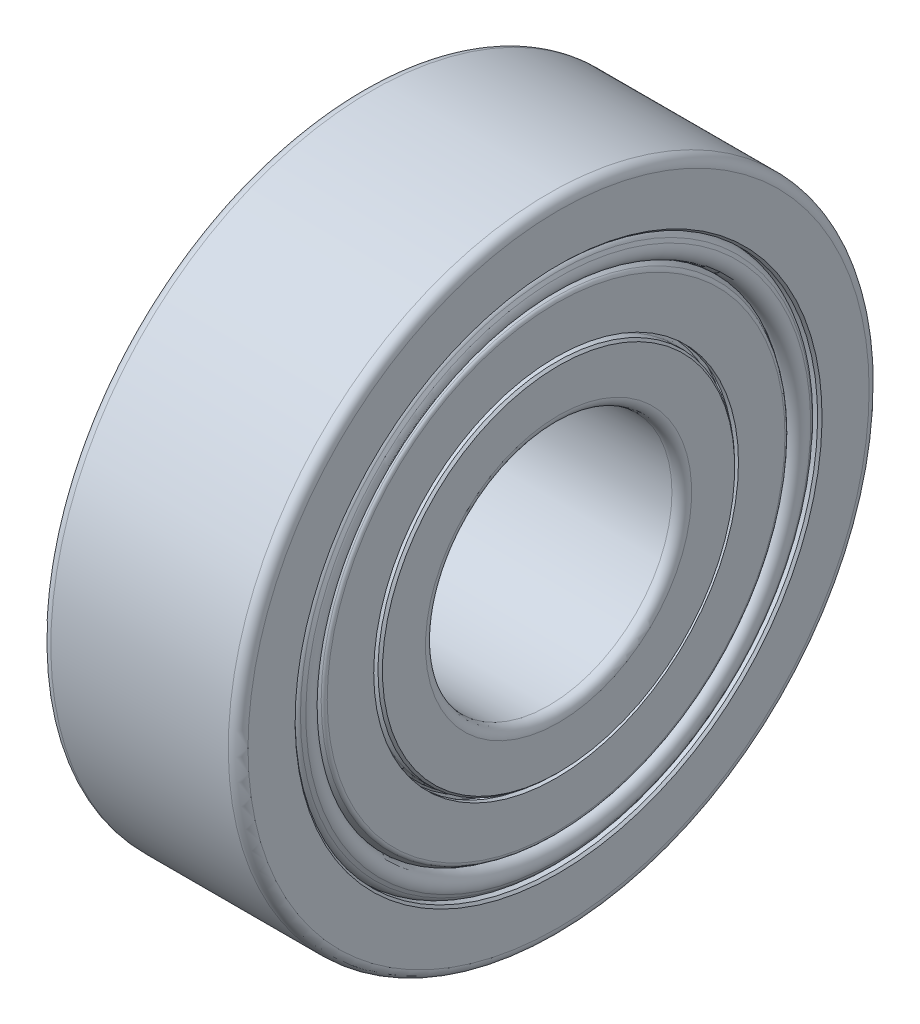
SolidWorks part; units mm, degrees
ref_plane "Front Plane" through (0, 0, 0) normal (0, 0, 1) x (1, 0, 0)
ref_plane "Top Plane" through (0, 0, 0) normal (0, 1, 0) x (1, 0, 0)
ref_plane "Right Plane" through (0, 0, 0) normal (1, 0, 0) x (0, 0, -1)
sketch "Sketch1" plane through (0, 0, 0) normal (1, 0, 0) x (0, 0, -1)
  line L0 (0, 6.5) -> (0, 6.3) construction
  line L1 (0, 2.5) -> (0, 2.7) construction
  circle A0 centre (0, 0) radius 6.5
  circle A1 centre (0, 0) radius 2.5
  circle A2 centre (0, 0) radius 5.3 construction
  circle A3 centre (0, 0) radius 3.7 construction
  dimension "OD" = 13
  dimension "ID" = 5
  dimension "Outer Ring ID" = 10.6
  dimension "Inner Ring OD" = 7.4
  dimension "Radius" = 0.2
sketch "Sketch2" plane through (0, 0, 0) normal (0, 0, 1) x (1, 0, 0)
  line L0 (-2, 6.5) -> (2, 6.5) construction
  point P3 (0, 6.5)
  dimension "Width" = 4
sketch "Sketch3" plane through (0, 0, 0) normal (0, 0, 1) x (1, 0, 0)
  line L0 (-1.8, 6.5) -> (1.8, 6.5)
  line L1 (-2, 6.3) -> (-2, 5.345)
  line L2 (2, 6.3) -> (2, 5.345)
  line L3 (-1.955, 5.3) -> (-1.7, 5.3)
  line L4 (-1.955, 3.6184) -> (-2, 3.5734)
  line L5 (-1.7891, 3.6184) -> (-1.955, 3.6184)
  line L6 (2, 5.345) -> (1.955, 5.3)
  line L7 (0, 6.5) -> (0, 5.3) construction
  line L8 (-2, 5.345) -> (-1.955, 5.3)
  line L9 (1.955, 3.6184) -> (1.955, 3.7) construction
  line L10 (-1.6625, 3.7) -> (-1.6625, 3.772)
  line L11 (-1.8, 2.5) -> (1.8, 2.5)
  line L12 (-2, 2.7) -> (-2, 3.5734)
  line L13 (2, 2.7) -> (2, 3.5734)
  line L14 (-1.6625, 3.7) -> (1.6625, 3.7) construction
  line L15 (1.6625, 3.7) -> (1.6625, 3.3667) construction
  line L16 (1.6625, 3.3667) -> (1.6625, 3.0333) construction
  line L17 (1.6625, 3.7) -> (1.6625, 3.6184) construction
  line L18 (1.6625, 3.6184) -> (1.955, 3.6184) construction
  line L19 (1.955, 3.6184) -> (2, 3.5734)
  line L20 (1.7891, 3.6184) -> (1.955, 3.6184)
  line L21 (1.6625, 3.0333) -> (1.6625, 2.7) construction
  line L22 (-1.8, 0) -> (1.8, 0) construction
  line L23 (1.7, 5.3) -> (1.7, 5.372)
  line L24 (1.7, 5.372) -> (-1.7, 5.372)
  line L25 (-1.7, 5.3) -> (-1.7, 5.372)
  line L26 (1.7, 5.3) -> (1.955, 5.3)
  line L27 (-1.6625, 3.772) -> (1.6625, 3.772)
  line L28 (1.6625, 3.772) -> (1.6625, 3.7)
  arc A0 (-2, 6.3) -> (-1.8, 6.5) centre (-1.8, 6.3) cw
  arc A1 (1.8, 6.5) -> (2, 6.3) centre (1.8, 6.3) cw
  arc A2 (-2, 2.7) -> (-1.8, 2.5) centre (-1.8, 2.7) ccw
  arc A3 (1.8, 2.5) -> (2, 2.7) centre (1.8, 2.7) ccw
  arc A4 (1.6625, 3.7) -> (1.7891, 3.6184) centre (1.7891, 3.7574) ccw
  arc A5 (-1.6625, 3.7) -> (-1.7891, 3.6184) centre (-1.7891, 3.7574) cw
  point P7 (-2, 6.5)
  point P15 (2, 6.5)
  point P30 (0, 3.7)
  point P48 (0, 5.372)
  dimension "D1" = 0.2
  dimension "D4" = 0.2
  dimension "D2" = 135
  dimension "D3" = 0.045
  dimension "D5" = 135
  dimension "D7" = 0.3375
  dimension "D9" = 0.072
  dimension "D10" = 0.3
  dimension "D8" = 0.1266
  dimension "D6" = 0.1266
revolve "Revolve1" add sketch "Sketch3" angle 360 about L22
sketch "Sketch4" plane through (0, 0, 0) normal (0, 0, 1) x (1, 0, 0)
  line L6 (1.7433, 4.9068) -> (1.6933, 4.9357) construction
  line L7 (1.6433, 5.08) -> (1.6433, 4.8837)
  line L8 (1.6533, 4.8664) -> (1.905, 4.7211)
  line L9 (1.95, 4.6431) -> (1.95, 3.7)
  line L10 (2, -6.3) -> (2, 6.3) construction
  line L11 (1.95, 3.7) -> (1.87, 3.7) construction
  line L12 (1.9233, 5.0107) -> (1.95, 5.0107) construction
  line L15 (1.6933, 4.9357) -> (1.6533, 4.8664) construction
  line L18 (1.8673, 5.14) -> (1.9073, 5.0707)
  line L20 (1.7, 5.3) -> (1.955, 5.3) construction
  arc A0 (1.6433, 5.08) -> (1.8673, 5.14) centre (1.7633, 5.08) cw
  arc A1 (1.9073, 5.0707) -> (1.7433, 4.9068) centre (1.8033, 5.0107) cw construction
  arc A2 (1.905, 4.7211) -> (1.95, 4.6431) centre (1.86, 4.6431) cw
  arc A3 (1.6433, 4.8837) -> (1.6533, 4.8664) centre (1.6633, 4.8837) ccw
  arc A4 (1.9073, 5.0707) -> (1.8033, 4.8907) centre (1.8033, 5.0107) cw
  point P18 (1.6625, 3.7)
  point P28 (1.95, 4.6951)
  point P31 (1.6433, 4.8722)
  dimension "D8" = 0.09
  dimension "D9" = 0.02
  dimension "D6" = 0.12
  dimension "D1" = 0.05
  dimension "D3" = 0.08
  dimension "D2" = 0.08
  dimension "D7" = 30
  dimension "D4" = 120
  dimension "D12" = 0.0267
  dimension "D5" = 0.1
revolve "Revolve-Thin1" add sketch "Sketch4" angle 360 about L22
mirror "Mirror2" about plane through (0, 0, 0) normal (1, 0, 0) of bodies 106
delete or keep bodies "Body-Delete/Keep 1" type delete bodies bodies 113
mirror "Mirror1" about plane through (0, 0, 0) normal (1, 0, 0) of bodies 106 112
equation "\"D4@Sketch3\"=\"D1@Sketch3\""
equation "\"D1@Sketch3\"=\"Radius@Sketch1\""
equation "\"D8@Sketch4\"=\"D3@Sketch4\"*1.125"
equation "\"D9@Sketch4\"=\"D3@Sketch4\"*.25"
equation "\"Outer Ring ID@Sketch1\"=\"OD@Sketch1\"-(((\"OD@Sketch1\"-\"ID@Sketch1\")/2)*.3*2)"
equation "\"Inner Ring OD@Sketch1\"=\"ID@Sketch1\"+(((\"OD@Sketch1\"-\"ID@Sketch1\")/2)*.3*2)"
equation "\"Radius@Sketch1\"=\"Width@Sketch2\"*.05"
equation "\"D3@Sketch4\"=\"Width@Sketch2\"*.02"
equation "\"D2@Sketch4\"=\"D3@Sketch4\""
equation "\"D12@Sketch4\"=\"D3@Sketch4\"/3"
equation "\"D6@Sketch4\"=((\"Outer Ring ID@Sketch1\"-\"Inner Ring OD@Sketch1\")/2)*.075"
equation "\"D10@Sketch3\"=\"Width@Sketch2\"*.075"
equation "\"D9@Sketch3\"=((\"OD@Sketch1\"-\"Outer Ring ID@Sketch1\")/2)*.06"
equation "\"D3@Sketch3\"=\"D9@Sketch3\"*.625"
equation "\"D7@Sketch3\"=\"D10@Sketch3\"*1.125"
equation "\"D6@Sketch3\"=\"D7@Sketch3\"*.375"
equation "\"D8@Sketch3\"=\"D6@Sketch3\""
equation "\"D1@Sketch4\"=\"D3@Sketch4\"*.625"
equation "\"D5@Sketch4\"=((\"Outer Ring ID@Sketch1\"-\"Inner Ring OD@Sketch1\")/2)*.0625"
equation "\"D3@Revolve-Thin1\"=\"D5@Sketch4\""
